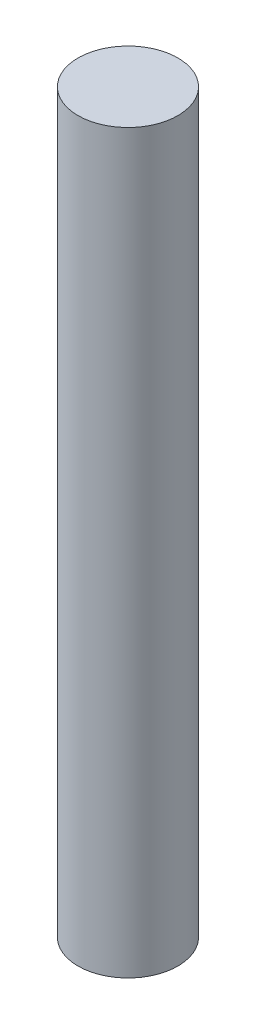
SolidWorks part; units mm, degrees
ref_plane "Front Plane" through (0, 0, 0) normal (0, 0, 1) x (1, 0, 0)
ref_plane "Top Plane" through (0, 0, 0) normal (0, 1, 0) x (1, 0, 0)
ref_plane "Right Plane" through (0, 0, 0) normal (1, 0, 0) x (0, 0, -1)
sketch "Sketch1" plane through (0, 0, 0) normal (0, 1, 0) x (1, 0, 0)
  circle A0 centre (0, 0) radius 4
  dimension "D1" = 8
extrude "Boss-Extrude1" add sketch "Sketch1" along normal blind 59
